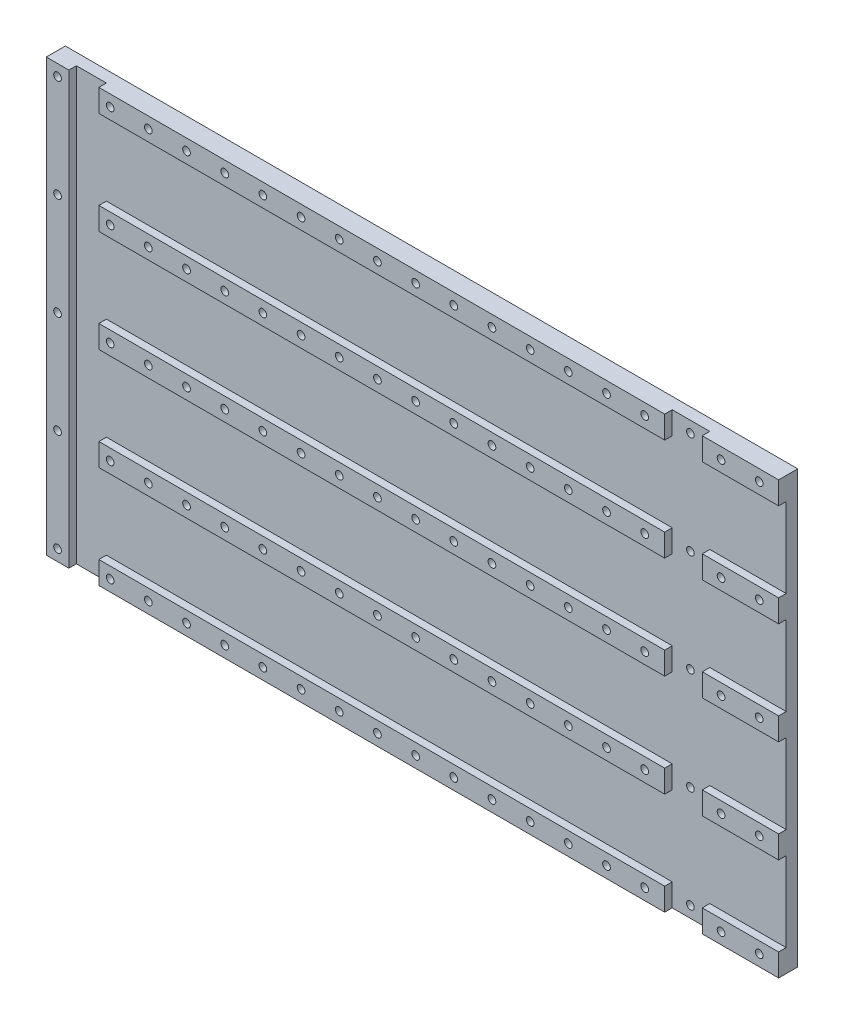
SolidWorks part; units mm, degrees
ref_plane "Front Plane" through (0, 0, 0) normal (0, 0, 1) x (1, 0, 0)
ref_plane "Top Plane" through (0, 0, 0) normal (0, 1, 0) x (1, 0, 0)
ref_plane "Right Plane" through (0, 0, 0) normal (1, 0, 0) x (0, 0, -1)
sketch "Master Sketch" plane through (0, 0, 0) normal (0, 0, 1) x (1, 0, 0)
  line L0 (15, 287) -> (15, 0) construction
  line L1 (0, 0) -> (487.2, 0) construction
  line L2 (0, 0) -> (0, 287) construction
  line L3 (0, 287) -> (487.2, 287) construction
  line L4 (487.2, 0) -> (487.2, 287) construction
  line L5 (0, 272) -> (487.2, 272) construction
  line L6 (0, 219) -> (487.2, 219) construction
  line L7 (0, 204) -> (487.2, 204) construction
  line L8 (0, 151) -> (487.2, 151) construction
  line L9 (0, 136) -> (487.2, 136) construction
  line L10 (0, 83) -> (487.2, 83) construction
  line L11 (0, 68) -> (487.2, 68) construction
  line L12 (0, 15) -> (487.2, 15) construction
  line L13 (35, 287) -> (35, 0) construction
  dimension "D1" = 15
  dimension "D2" = 53
  dimension "D3" = 15
  dimension "D4" = 53
  dimension "D5" = 15
  dimension "D6" = 53
  dimension "D7" = 15
  dimension "D8" = 53
  dimension "D9" = 15
  dimension "D10" = 15
  dimension "D11" = 20
  dimension "D12" = 452.2
sketch "Sketch2" plane through (0, 0, 0) normal (0, 0, 1) x (1, 0, 0)
  line L1 (0, 287) -> (487.2, 287)
  line L2 (0, 287) -> (0, 0)
  line L3 (0, 0) -> (487.2, 0)
  line L4 (487.2, 287) -> (487.2, 0)
extrude "Extrude1" add sketch "Sketch2" along normal blind 12.7
sketch "Sketch3" plane through (0, 0, 12.7) normal (0, 0, 1) x (1, 0, 0)
  line L0 (35, 272) -> (411.4, 272)
  line L1 (15, 287) -> (35, 287)
  line L2 (15, 287) -> (15, 0)
  line L3 (15, 0) -> (35, 0)
  line L4 (35, 287) -> (35, 272)
  line L5 (487.2, 15) -> (436.4, 15)
  line L6 (487.2, 15) -> (487.2, 68)
  line L7 (487.2, 68) -> (436.4, 68)
  line L8 (0, 272) -> (487.2, 272) construction
  line L9 (487.2, 83) -> (436.4, 83)
  line L10 (487.2, 83) -> (487.2, 136)
  line L11 (487.2, 136) -> (436.4, 136)
  line L12 (0, 219) -> (487.2, 219) construction
  line L13 (487.2, 151) -> (436.4, 151)
  line L14 (487.2, 151) -> (487.2, 204)
  line L15 (487.2, 204) -> (436.4, 204)
  line L16 (0, 204) -> (487.2, 204) construction
  line L17 (0, 136) -> (487.2, 136) construction
  line L18 (0, 68) -> (487.2, 68) construction
  line L19 (487.2, 287) -> (0, 287) construction
  line L20 (487.2, 272) -> (487.2, 219)
  line L21 (35, 219) -> (35, 204)
  line L22 (35, 219) -> (411.4, 219)
  line L23 (411.4, 287) -> (436.4, 287)
  line L24 (35, 151) -> (35, 136)
  line L25 (411.4, 287) -> (411.4, 272)
  line L26 (411.4, 0) -> (436.4, 0)
  line L27 (35, 83) -> (35, 68)
  line L28 (436.4, 287) -> (436.4, 272)
  line L29 (0, 0) -> (487.2, 0) construction
  line L30 (35, 15) -> (35, 0)
  line L31 (487.2, 0) -> (487.2, 287) construction
  line L32 (411.4, 219) -> (411.4, 204)
  line L33 (436.4, 219) -> (436.4, 204)
  line L34 (436.4, 272) -> (487.2, 272)
  line L35 (436.4, 219) -> (487.2, 219)
  line L36 (411.4, 204) -> (35, 204)
  line L37 (411.4, 151) -> (35, 151)
  line L38 (411.4, 136) -> (35, 136)
  line L39 (411.4, 83) -> (35, 83)
  line L40 (411.4, 68) -> (35, 68)
  line L41 (411.4, 15) -> (35, 15)
  line L42 (411.4, 15) -> (411.4, 0)
  line L43 (436.4, 15) -> (436.4, 0)
  line L44 (411.4, 83) -> (411.4, 68)
  line L45 (436.4, 83) -> (436.4, 68)
  line L46 (411.4, 151) -> (411.4, 136)
  line L47 (436.4, 151) -> (436.4, 136)
  dimension "D1" = 25
  dimension "D2" = 50.8
extrude "Cut-Extrude1" cut sketch "Sketch3" against normal blind 5
sketch "Sketch4" plane through (0, 0, 12.7) normal (0, 0, 1) x (1, 0, 0)
  line L0 (42.5, 287) -> (42.5, 0) construction
  line L1 (487.2, 287) -> (436.4, 287) construction
  line L2 (35, 0) -> (411.4, 0) construction
  line L3 (35, 279.5) -> (487.2, 279.5) construction
  line L4 (35, 272) -> (35, 287) construction
  line L5 (487.2, 272) -> (487.2, 287) construction
  line L6 (35, 211.5) -> (487.2, 211.5) construction
  line L7 (35, 204) -> (35, 219) construction
  line L8 (487.2, 204) -> (487.2, 219) construction
  line L9 (35, 143.5) -> (487.2, 143.5) construction
  line L10 (35, 136) -> (35, 151) construction
  line L11 (487.2, 136) -> (487.2, 151) construction
  line L12 (35, 75.5) -> (487.2, 75.5) construction
  line L13 (35, 68) -> (35, 83) construction
  line L14 (487.2, 68) -> (487.2, 83) construction
  line L15 (35, 7.5) -> (487.2, 7.5) construction
  line L16 (35, 0) -> (35, 15) construction
  line L17 (487.2, 0) -> (487.2, 15) construction
  circle A0 centre (42.5, 279.5) radius 2.5527
  circle A1 centre (42.5, 211.5) radius 2.5527
  circle A2 centre (42.5, 143.5) radius 2.5527
  circle A3 centre (42.5, 75.5) radius 2.5527
  circle A4 centre (42.5, 7.5) radius 2.5527
  dimension "D2" = 5.1054
  dimension "D1" = 7.5
extrude "Cut-Extrude2" cut sketch "Sketch4" against normal through all
pattern_linear "LPattern1" count 18 spacing 25.4 along (1, 0, 0) of "Cut-Extrude2"
sketch "Sketch6" plane through (0, 0, 12.7) normal (0, 0, 1) x (1, 0, 0)
  line L0 (7.5, 287) -> (7.5, 0) construction
  line L1 (15, 287) -> (0, 287) construction
  line L2 (0, 0) -> (15, 0) construction
  line L3 (35, 279.5) -> (0, 279.5) construction
  line L4 (35, 272) -> (35, 287) construction
  line L5 (0, 287) -> (0, 0) construction
  line L6 (35, 211.5) -> (0, 211.5) construction
  line L7 (35, 219) -> (35, 204) construction
  line L8 (35, 143.5) -> (0, 143.5) construction
  line L9 (35, 151) -> (35, 136) construction
  line L10 (35, 75.5) -> (0, 75.5) construction
  line L11 (35, 83) -> (35, 68) construction
  line L12 (35, 7.5) -> (0, 7.5) construction
  line L13 (35, 0) -> (35, 15) construction
  circle A0 centre (7.5, 279.5) radius 2.5527
  circle A1 centre (7.5, 211.5) radius 2.5527
  circle A2 centre (7.5, 143.5) radius 2.5527
  circle A3 centre (7.5, 75.5) radius 2.5527
  circle A4 centre (7.5, 7.5) radius 2.5527
  circle A5 centre (42.5, 279.5) radius 2.5527 construction
extrude "Cut-Extrude3" cut sketch "Sketch6" against normal through all
